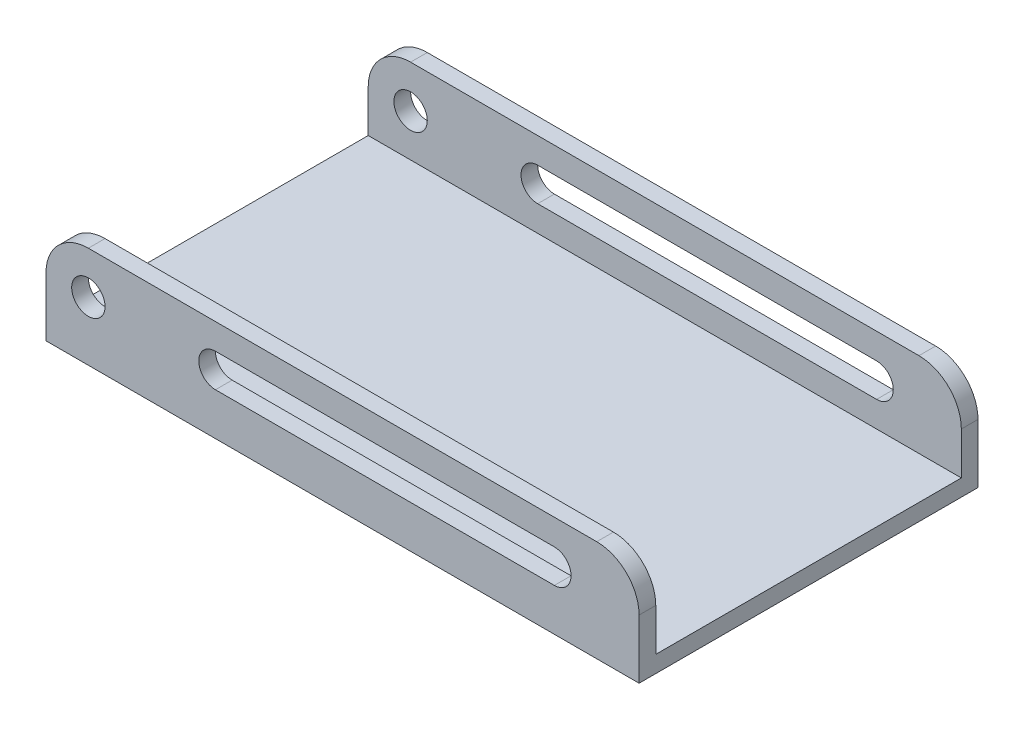
SolidWorks part; units mm, degrees
material "Stainless Steel (ferritic)"
ref_plane "Front Plane" through (0, 0, 0) normal (0, 0, 1) x (1, 0, 0)
ref_plane "Top Plane" through (0, 0, 0) normal (0, 1, 0) x (1, 0, 0)
ref_plane "Right Plane" through (0, 0, 0) normal (1, 0, 0) x (0, 0, -1)
sketch "Sketch2" plane through (0, 0, 0) normal (0, 1, 0) x (1, 0, 0)
  line L1 (0, 0) -> (177.8, 0)
  line L2 (0, 0) -> (0, 101.6)
  line L3 (0, 101.6) -> (177.8, 101.6)
  line L4 (177.8, 0) -> (177.8, 101.6)
  dimension "D1" = 177.8
  dimension "D2" = 101.6
extrude "Boss-Extrude1" add sketch "Sketch2" along normal blind 5
sketch "Sketch3" plane through (0, 5, 0) normal (0, 1, 0) x (1, 0, 0)
  line L5 (177.8, 0) -> (177.8, 101.6) construction
  line L10 (0, 0) -> (177.8, 0)
  line L11 (0, 0) -> (0, 5)
  line L12 (0, 5) -> (177.8, 5)
  line L13 (177.8, 0) -> (177.8, 5)
  line L15 (0, 101.6) -> (177.8, 101.6)
  line L16 (0, 101.6) -> (0, 96.6)
  line L17 (0, 96.6) -> (177.8, 96.6)
  line L18 (177.8, 101.6) -> (177.8, 96.6)
  dimension "D1" = 5
extrude "Boss-Extrude3" add sketch "Sketch3" along normal blind 25.4
sketch "Sketch4" plane through (0, 0, 0) normal (0, 0, 1) x (1, 0, 0)
  line L0 (0, 5) -> (0, 30.4) construction
  line L1 (0, 17.7) -> (177.8, 17.7) construction
  line L2 (177.8, 30.4) -> (177.8, 0) construction
  line L3 (50.8, 17.7) -> (152.4, 17.7) construction
  line L4 (50.8, 22.7) -> (152.4, 22.7)
  line L5 (50.8, 12.7) -> (152.4, 12.7)
  arc A0 (50.8, 22.7) -> (50.8, 12.7) centre (50.8, 17.7) ccw
  arc A1 (152.4, 12.7) -> (152.4, 22.7) centre (152.4, 17.7) ccw
  circle A2 centre (12.7, 17.7) radius 5
  point P10 (101.6, 17.7)
  dimension "D2" = 10
  dimension "D1" = 10
  dimension "D3" = 12.7
  dimension "D4" = 25.4
  dimension "D5" = 38.1
extrude "Cut-Extrude1" cut sketch "Sketch4" against normal through all
fillet "Fillet1" radius 12.7 4 edges at (0, 30.4, -99.1) (0, 30.4, -2.5) (177.8, 30.4, -99.1) (177.8, 30.4, -2.5)
